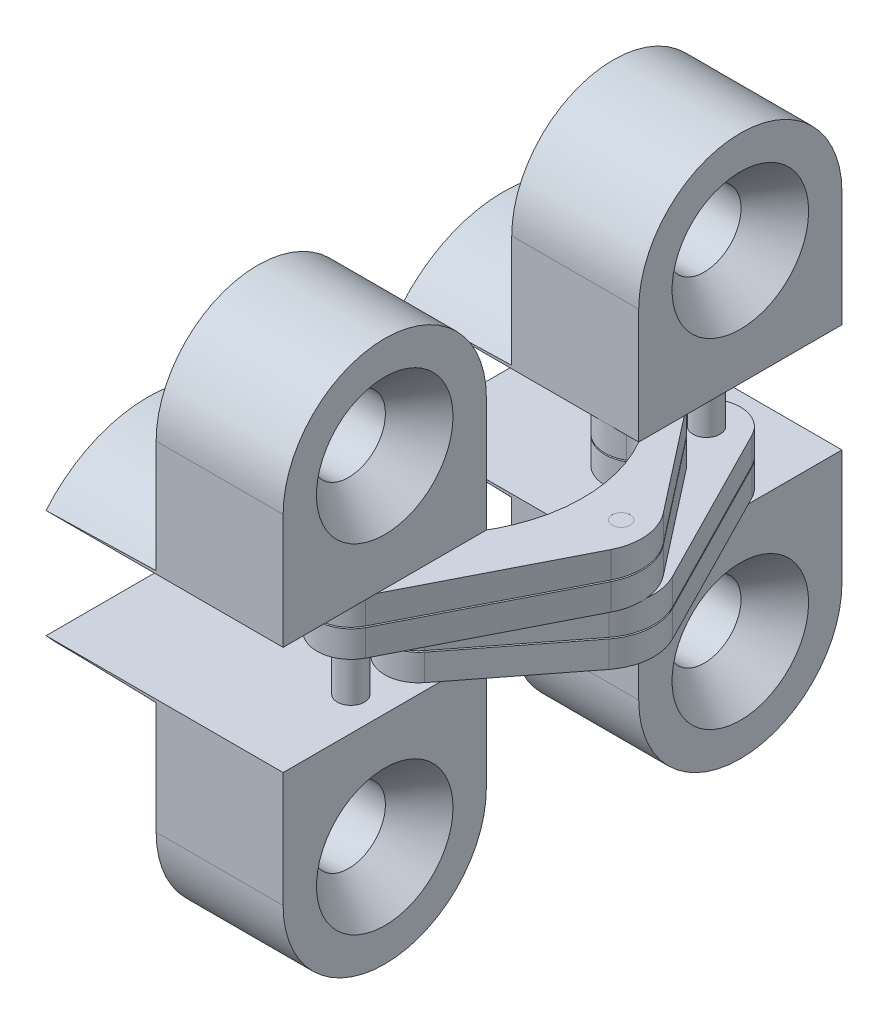
SolidWorks part; units mm, degrees
ref_plane "Front" through (0, 0, 0) normal (0, 0, 1) x (1, 0, 0)
ref_plane "Top" through (0, 0, 0) normal (0, 1, 0) x (1, 0, 0)
ref_plane "Right" through (0, 0, 0) normal (1, 0, 0) x (0, 0, -1)
sketch "Sketch1" plane through (0, 0, 0) normal (1, 0, 0) x (0, 0, -1)
  line L0 (-8.3344, 0) -> (8.3344, 0) construction
  line L1 (-11.9062, 2.54) -> (-4.7625, -2.54) construction
  line L2 (-11.9062, 2.54) -> (-4.7625, 2.54) construction
  line L3 (-11.9062, 2.54) -> (-11.9062, -2.54) construction
  line L4 (-11.9062, -2.54) -> (-4.7625, -2.54) construction
  line L5 (-4.7625, 2.54) -> (-4.7625, -2.54) construction
  line L6 (4.7625, 2.54) -> (11.9063, 2.54) construction
  line L7 (4.7625, 2.54) -> (4.7625, -2.54) construction
  line L8 (4.7625, -2.54) -> (11.9062, -2.54) construction
  line L9 (11.9063, 2.54) -> (11.9062, -2.54) construction
  line L10 (4.7625, 2.54) -> (11.9062, -2.54) construction
  line L11 (-4.7625, 2.54) -> (-5.9531, 2.54) construction
  line L12 (-5.9531, 2.54) -> (-5.9531, 3.7306) construction
  line L13 (-5.9531, 3.7306) -> (-7.1438, 3.7306) construction
  line L14 (-7.1438, 3.7306) -> (-7.1438, 2.54) construction
  line L15 (-7.1438, 2.54) -> (-11.9062, 2.54) construction
  line L16 (-11.9062, -2.54) -> (-7.1438, -2.54) construction
  line L17 (-7.1438, -2.54) -> (-7.1438, -3.7306) construction
  line L18 (-7.1438, -3.7306) -> (-5.9531, -3.7306) construction
  line L19 (-5.9531, -3.7306) -> (-5.9531, -2.54) construction
  line L20 (-5.9531, -2.54) -> (-4.7625, -2.54) construction
  line L21 (4.7625, 2.54) -> (5.9531, 2.54) construction
  line L22 (5.9531, 2.54) -> (5.9531, 3.7306) construction
  line L23 (5.9531, 3.7306) -> (7.1437, 3.7306) construction
  line L24 (7.1437, 3.7306) -> (7.1438, 2.54) construction
  line L25 (7.1438, 2.54) -> (11.9063, 2.54) construction
  line L26 (4.7625, -2.54) -> (5.9531, -2.54) construction
  line L27 (5.9531, -2.54) -> (5.9531, -3.7306) construction
  line L28 (5.9531, -3.7306) -> (7.1438, -3.7306) construction
  line L29 (7.1438, -3.7306) -> (7.1438, -2.54) construction
  line L30 (7.1438, -2.54) -> (11.9062, -2.54) construction
  line L31 (-8.3344, 0) -> (-4.7625, 0) construction
  line L32 (4.7625, 0) -> (8.3344, 0) construction
  line L33 (-6.5484, 3.7306) -> (-6.5484, 0) construction
  line L34 (6.5484, 3.7306) -> (6.5484, 0) construction
  line L35 (-3.5719, 7.9375) -> (-3.5719, -7.9375) construction
  line L36 (-13.0969, 7.9375) -> (-13.0969, -7.9375) construction
  line L37 (3.5719, 7.9375) -> (3.5719, -7.9375) construction
  line L38 (13.0969, 7.9375) -> (13.0969, -7.9375) construction
  line L39 (8.3344, 12.7) -> (-8.3344, 12.7) construction
  line L40 (-8.3344, -12.7) -> (8.3344, -12.7) construction
  line L41 (-13.0969, 7.9375) -> (-13.0969, -7.9375)
  line L42 (-3.5719, 7.9375) -> (-3.5719, -7.9375)
  line L43 (3.5719, 7.9375) -> (3.5719, -7.9375)
  line L44 (13.0969, 7.9375) -> (13.0969, -7.9375)
  line L45 (-4.7625, 2.54) -> (-4.7625, 0) construction
  line L46 (-4.7625, 1.27) -> (4.7625, 1.27) construction
  line L47 (-4.7625, 1.27) -> (-4.7625, -1.27) construction
  line L48 (-4.7625, -1.27) -> (4.7625, -1.27) construction
  line L49 (4.7625, 1.27) -> (4.7625, -1.27) construction
  arc A2 (-13.0969, 7.9375) -> (-3.5719, 7.9375) centre (-8.3344, 7.9375) cw
  arc A3 (-13.0969, -7.9375) -> (-3.5719, -7.9375) centre (-8.3344, -7.9375) ccw
  arc A4 (3.5719, 7.9375) -> (13.0969, 7.9375) centre (8.3344, 7.9375) cw
  arc A5 (3.5719, -7.9375) -> (13.0969, -7.9375) centre (8.3344, -7.9375) ccw
  point P45 (-3.5719, 0)
  point P54 (4.7625, 0.8467)
  point P55 (0, -12.7)
  point P56 (4.7625, 1.6933)
  point P57 (4.7625, -0.8467)
  point P58 (4.7625, -1.6933)
  dimension "D1" = 7.1438
  dimension "D2" = 5.08
  dimension "A" = 16.6687
  dimension "Leaf Ht" = 25.4
  dimension "Leaf Wd" = 9.525
  dimension "D3" = 0.8467
  dimension "D4" = 0.8467
  dimension "D5" = 0.8467
  dimension "D6" = 0.8467
extrude "Extrude1" add sketch "Sketch1" against normal blind 11.1125
sketch "Sketch16" plane through (0, 0, 0) normal (1, 0, 0) x (0, 0, -1)
  line L0 (-13.0969, 7.9375) -> (-13.0969, -7.9375) construction
  line L1 (-13.0969, 2.54) -> (13.0969, 2.54)
  line L2 (-13.0969, 2.54) -> (-13.0969, -2.54)
  line L3 (-13.0969, -2.54) -> (13.0969, -2.54)
  line L4 (13.0969, 2.54) -> (13.0969, -2.54)
  line L5 (13.0969, 7.9375) -> (13.0969, -7.9375) construction
  line L6 (-11.9062, 2.54) -> (-4.7625, 2.54) construction
  line L7 (4.7625, -2.54) -> (11.9062, -2.54) construction
extrude "Cut-Extrude1" cut sketch "Sketch16" against normal through all
ref_plane "Plane2" through (0, 0, 8.3344) normal (0, 0, 1) x (1, 0, 0)
ref_plane "Plane3" through (0, 0, -8.3344) normal (0, 0, 1) x (1, 0, 0)
ref_plane "Plane1" through (0, 1.27, 0) normal (0, 1, 0) x (-1, 0, 0)
sketch "Sketch4" plane through (0, 1.27, 0) normal (0, 1, 0) x (-1, 0, 0)
  line L0 (0, 8.3344) -> (0, -8.3344) construction
  line L1 (11.1125, 3.5719) -> (0, 3.5719) construction
  line L2 (-4.445, 0) -> (0.1733, 9.0556) construction
  line L4 (0.1733, -9.0556) -> (-4.445, 0) construction
  line L5 (-4.445, 0) -> (0.3352, 6.1351) construction
  line L8 (1.5875, 5.1594) -> (0.7938, 3.7846) construction
  line L9 (-3.175, 0) -> (-4.445, 0) construction
  line L11 (11.1125, 9.9219) -> (0, 9.9219) construction
  line L12 (1.5875, -8.3344) -> (1.5875, 8.3344) construction
  line L15 (11.1125, -3.5719) -> (0, -3.5719) construction
  line L18 (11.1125, 3.5719) -> (11.1125, 13.0969) construction
  line L19 (0, 13.0969) -> (0, 3.5719) construction
  line L20 (11.1125, 13.0969) -> (0, 13.0969) construction
  arc A0 (0.3352, 6.1351) -> (0.7938, 3.7846) centre (1.5875, 5.1594) cw construction
  arc A1 (0, -3.5719) -> (0, 3.5719) centre (6.1867, 0) cw construction
  arc A2 (0, 3.5719) -> (0.7938, 3.7846) centre (0.5032, 3.2813) cw construction
  circle A3 centre (1.5875, 8.3344) radius 0.635 construction
  circle A5 centre (1.5875, -8.3344) radius 1.5875 construction
  circle A8 centre (-2.7517, 0) radius 0.4233 construction
  circle A9 centre (1.5875, -8.3344) radius 0.635 construction
  circle A10 centre (1.5875, 5.1594) radius 0.635 construction
  circle A12 centre (1.5875, 8.3344) radius 1.5875 construction
  circle A14 centre (1.5875, -5.1594) radius 1.5875 construction
  dimension "D1" = 4.445
  dimension "D2" = 3.175
  dimension "D3" = 1.27
  dimension "D5" = 1.27
  dimension "D6" = 0.8467
  dimension "D7" = 3.175
  dimension "D8" = 30
sketch "Sketch5" plane through (0, 1.27, 0) normal (0, 1, 0) x (-1, 0, 0)
  line L0 (0.1733, -9.0556) -> (-4.445, 0) construction
  line L1 (0.1733, -9.0556) -> (-4.445, 0)
  line L2 (-4.445, 0) -> (0.3352, 6.1351)
  line L3 (2.8447, -7.365) -> (0.5293, -4.362)
  arc A0 (0.1733, -9.0556) -> (2.8447, -7.365) centre (1.5875, -8.3344) ccw
  arc A1 (0, 3.5719) -> (0.5293, -4.362) centre (6.1867, 0) ccw
  arc A2 (0.7938, 3.7846) -> (0.3352, 6.1351) centre (1.5875, 5.1594) ccw
  arc A3 (0, 3.5719) -> (0.7938, 3.7846) centre (0.5032, 3.2813) cw
  arc A4 (0, 3.5719) -> (0, -3.5719) centre (6.1867, 0) ccw construction
  circle A8 centre (1.5875, -8.3344) radius 0.635
  circle A9 centre (-2.7517, 0) radius 0.4233
  circle A12 centre (1.5875, 5.1594) radius 0.635
  circle A13 centre (1.5875, 5.1594) radius 0.635 construction
  circle A15 centre (1.5875, -8.3344) radius 0.635 construction
  arc A16 (0.7938, 3.7846) -> (0.3352, 6.1351) centre (1.5875, 5.1594) ccw construction
  circle A18 centre (-2.7517, 0) radius 0.4233 construction
  arc A21 (0.7938, 3.7846) -> (0, 3.5719) centre (0.5032, 3.2813) ccw construction
extrude "Extrude3" [suppressed] add sketch "Sketch5" along normal up to vertex separate body
sketch "Sketch6" [suppressed] plane through (0, 3.5719, 0) normal (0, 1, 0) x (-1, 0, 0)
  line L0 (-4.6037, 0) -> (0.1769, 9.261) construction
  line L1 (0.563, 4.61) -> (2.8438, 7.5623)
  line L3 (0.3356, -6.334) -> (-4.6037, 0)
  line L4 (-4.6037, 0) -> (0.1769, 9.261)
  line L5 (-4.6037, 0) -> (0.3356, 6.334) construction
  line L6 (1.5875, -8.5328) -> (1.5875, 8.5328) construction
  arc A0 (0.1769, 9.261) -> (2.8438, 7.5623) centre (1.5875, 8.5328) cw
  arc A2 (0.3356, -6.334) -> (0.7938, -3.983) centre (1.5875, -5.3578) ccw
  circle A3 centre (1.5875, 8.5328) radius 1.5875 construction
  arc A4 (0, -3.7703) -> (0.563, 4.61) centre (6.5304, 0) cw
  arc A6 (0, 3.7703) -> (0, -3.7703) centre (6.5304, 0) ccw construction
  arc A7 (0.7938, -3.983) -> (0, -3.7703) centre (0.5032, -3.4798) cw
  circle A8 centre (1.5875, -5.3578) radius 0.635
  circle A9 centre (1.5875, 5.3578) radius 0.635 construction
  circle A10 centre (-2.9104, 0) radius 0.4233
  circle A12 centre (1.5875, 8.5328) radius 0.635
  arc A13 (0.7938, 3.983) -> (0, 3.7703) centre (0.5032, 3.4798) ccw construction
  circle A16 centre (-2.9104, 0) radius 0.4233 construction
extrude "Extrude13" [suppressed] add sketch "Sketch6" against normal up to vertex separate body
sketch "Sketch7" [suppressed] plane through (0, 0, 0) normal (0, 1, 0) x (-1, 0, 0)
  line L0 (0.1769, -9.261) -> (-4.6037, 0) construction
  line L1 (0.3356, 6.334) -> (-4.6037, 0)
  line L2 (-4.6037, 0) -> (0.1769, -9.261)
  line L3 (-4.6037, 0) -> (0.3356, 6.334) construction
  line L4 (2.8438, -7.5623) -> (0.563, -4.61)
  arc A0 (0.3356, 6.334) -> (0.7938, 3.983) centre (1.5875, 5.3578) cw
  circle A1 centre (1.5875, -8.5328) radius 0.635 construction
  arc A2 (0.1769, -9.261) -> (2.8438, -7.5623) centre (1.5875, -8.5328) ccw
  arc A4 (0.563, -4.61) -> (0, 3.7703) centre (6.5304, 0) cw
  arc A5 (0, 3.7703) -> (0.7938, 3.983) centre (0.5032, 3.4798) cw
  arc A6 (0.7938, 3.983) -> (0, 3.7703) centre (0.5032, 3.4798) ccw construction
  circle A7 centre (1.5875, 5.3578) radius 0.635 construction
  circle A8 centre (-2.9104, 0) radius 0.4233 construction
  circle A9 centre (1.5875, 5.3578) radius 0.635
  arc A10 (0, 3.7703) -> (0, -3.7703) centre (6.5304, 0) ccw construction
  circle A15 centre (1.5875, -8.5328) radius 0.635
  circle A17 centre (-2.9104, 0) radius 0.4233
extrude "Extrude5" [suppressed] add sketch "Sketch7" against normal up to vertex separate body
sketch "Sketch17" [suppressed] plane through (0, -3.5719, 0) normal (0, -1, 0) x (1, 0, 0)
  line L0 (-0.3356, -6.334) -> (4.6037, 0)
  line L1 (4.6037, 0) -> (-0.1769, 9.261)
  line L2 (4.6037, 0) -> (-0.1769, 9.261) construction
  line L3 (-0.563, 4.61) -> (-2.8438, 7.5623)
  arc A0 (-0.3356, -6.334) -> (-0.7938, -3.983) centre (-1.5875, -5.3578) cw
  arc A1 (-2.8438, 7.5623) -> (-0.1769, 9.261) centre (-1.5875, 8.5328) cw
  arc A2 (0, -3.7703) -> (-0.563, 4.61) centre (-6.5304, 0) ccw
  arc A3 (-0.7938, -3.983) -> (-0.3356, -6.334) centre (-1.5875, -5.3578) ccw construction
  arc A6 (-0.7938, -3.983) -> (0, -3.7703) centre (-0.5032, -3.4798) ccw
  arc A7 (0, -3.7703) -> (0, 3.7703) centre (-6.5304, 0) ccw construction
  arc A8 (-0.7938, -3.983) -> (0, -3.7703) centre (-0.5032, -3.4798) ccw construction
  circle A9 centre (-1.5875, -5.3578) radius 0.635
  circle A10 centre (2.9104, 0) radius 0.4233
  circle A11 centre (-1.5875, 8.5328) radius 0.635
  circle A12 centre (-1.5875, 8.5328) radius 0.635 construction
  circle A13 centre (-1.5875, -5.3578) radius 0.635 construction
  circle A14 centre (2.9104, 0) radius 0.4233 construction
extrude "Extrude14" [suppressed] add sketch "Sketch17" along normal up to surface (3.5719 mm away) separate body
fillet "Fillet3" [suppressed] radius 2.54
fillet "Fillet4" [suppressed] radius 2.54
fillet "Fillet5" [suppressed] radius 2.54
fillet "Fillet6" [suppressed] radius 2.54
sketch "Sketch41" plane through (0, 0, 0) normal (1, 0, 0) x (0, 0, -1)
  line L0 (-13.0969, 7.9375) -> (-13.0969, -7.9375) construction
  line L1 (-13.0969, 1.7251) -> (13.0969, 1.7251)
  line L2 (-13.0969, 1.7251) -> (-13.0969, 1.6616)
  line L3 (-13.0969, 1.6616) -> (13.0969, 1.6616)
  line L4 (13.0969, 1.7251) -> (13.0969, 1.6616)
  line L5 (13.0969, 7.9375) -> (13.0969, -7.9375) construction
  line L6 (13.0969, 1.7251) -> (13.0969, 2.54) construction
  line L7 (-13.0969, 1.7251) -> (-13.0969, 2.54) construction
  line L8 (4.7625, 1.7251) -> (4.7625, 1.6616) construction
  line L9 (4.7625, 2.54) -> (4.7625, -2.54) construction
  line L10 (4.7625, 1.6616) -> (4.7625, 1.27) construction
  line L11 (-13.0969, 2.1484) -> (13.0969, 2.1484)
  line L12 (-13.0969, 2.1484) -> (-13.0969, 2.0849)
  line L13 (-13.0969, 2.0849) -> (13.0969, 2.0849)
  line L14 (13.0969, 2.1484) -> (13.0969, 2.0849)
  line L15 (-13.0969, 0.8784) -> (13.0969, 0.8784)
  line L16 (-13.0969, 0.8784) -> (-13.0969, 0.8149)
  line L17 (-13.0969, 0.8149) -> (13.0969, 0.8149)
  line L18 (13.0969, 0.8784) -> (13.0969, 0.8149)
  line L19 (-13.0969, 0.4551) -> (13.0969, 0.4551)
  line L20 (-13.0969, 0.4551) -> (-13.0969, 0.3916)
  line L21 (-13.0969, 0.3916) -> (13.0969, 0.3916)
  line L22 (13.0969, 0.4551) -> (13.0969, 0.3916)
  line L23 (-13.0969, -0.3916) -> (13.0969, -0.3916)
  line L24 (-13.0969, -0.3916) -> (-13.0969, -0.4551)
  line L25 (-13.0969, -0.4551) -> (13.0969, -0.4551)
  line L26 (13.0969, -0.3916) -> (13.0969, -0.4551)
  line L27 (-13.0969, -0.8149) -> (13.0969, -0.8149)
  line L28 (-13.0969, -0.8149) -> (-13.0969, -0.8784)
  line L29 (-13.0969, -0.8784) -> (13.0969, -0.8784)
  line L30 (13.0969, -0.8149) -> (13.0969, -0.8784)
  line L31 (-13.0969, -1.6616) -> (13.0969, -1.6616)
  line L32 (-13.0969, -1.6616) -> (-13.0969, -1.7251)
  line L33 (-13.0969, -1.7251) -> (13.0969, -1.7251)
  line L34 (13.0969, -1.6616) -> (13.0969, -1.7251)
  line L35 (-13.0969, -2.0849) -> (13.0969, -2.0849)
  line L36 (-13.0969, -2.0849) -> (-13.0969, -2.1484)
  line L37 (-13.0969, -2.1484) -> (13.0969, -2.1484)
  line L38 (13.0969, -2.0849) -> (13.0969, -2.1484)
  line L39 (4.7625, 2.1484) -> (4.7625, 2.54) construction
  line L40 (4.7625, 1.27) -> (4.7625, 0.8784) construction
  line L41 (4.7625, 0) -> (4.7625, 0.3916) construction
  line L42 (4.7625, 0) -> (4.7625, -0.3916) construction
  line L43 (4.7625, -0.8784) -> (4.7625, -1.27) construction
  line L44 (4.7625, -1.27) -> (4.7625, -1.6616) construction
  line L45 (4.7625, -2.54) -> (4.7625, -2.1484) construction
  dimension "D1" = 0.0635
  dimension "D2" = 0.0635
  dimension "D3" = 0.0635
  dimension "D4" = 0.0635
  dimension "D5" = 0.0635
  dimension "D6" = 0.0635
  dimension "D7" = 0.0635
  dimension "D8" = 0.0635
extrude "Cut-Extrude4" [suppressed] cut sketch "Sketch41" against normal through all and the other way through all
sketch "Sketch34" plane through (0, 2.54, 0) normal (0, -1, 0) x (1, 0, 0)
  line L0 (-0.1733, 9.0556) -> (4.445, 0)
  line L1 (-0.3352, -6.1351) -> (4.445, 0)
  line L2 (-0.5293, 4.362) -> (-2.8447, 7.365)
  arc A0 (-0.1733, 9.0556) -> (-2.8447, 7.365) centre (-1.5875, 8.3344) ccw
  circle A1 centre (-1.5875, 8.3344) radius 1.5875 construction
  arc A2 (-0.7938, -3.7846) -> (-0.3352, -6.1351) centre (-1.5875, -5.1594) ccw
  circle A3 centre (-1.5875, -5.1594) radius 1.5875 construction
  arc A4 (-0.3352, 6.1351) -> (-0.7938, 3.7846) centre (-1.5875, 5.1594) ccw construction
  arc A5 (-0.7938, -3.7846) -> (0, -3.5719) centre (-0.5032, -3.2813) ccw
  arc A6 (0, -3.5719) -> (-0.5293, 4.362) centre (-6.1867, 0) ccw
  arc A7 (0, -3.5719) -> (0, 3.5719) centre (-6.1867, 0) ccw construction
  circle A8 centre (-1.5875, 8.3344) radius 0.635
  circle A9 centre (-1.5875, 8.3344) radius 0.635 construction
  circle A10 centre (-1.5875, -5.1594) radius 0.635
  circle A11 centre (2.7517, 0) radius 0.4233
  circle A12 centre (2.7517, 0) radius 0.4233 construction
extrude "Extrude18" add sketch "Sketch34" along normal up to vertex (2.54 mm away) separate body up to point (0, 0, 4.7625)
sketch "Sketch35" plane through (0, 0, 0) normal (0, -1, 0) x (1, 0, 0)
  line L0 (-2.8447, -7.365) -> (-0.5293, -4.362)
  line L1 (-0.1733, -9.0556) -> (4.445, 0)
  line L2 (4.445, 0) -> (-0.3352, 6.1351)
  arc A0 (-2.8447, -7.365) -> (-0.1733, -9.0556) centre (-1.5875, -8.3344) ccw
  circle A1 centre (-1.5875, -8.3344) radius 1.5875 construction
  arc A2 (-0.7938, 3.7846) -> (-0.3352, 6.1351) centre (-1.5875, 5.1594) cw
  arc A3 (-0.3352, 6.1351) -> (-0.7938, 3.7846) centre (-1.5875, 5.1594) ccw construction
  arc A4 (-0.5293, -4.362) -> (0, 3.5719) centre (-6.1867, 0) ccw
  arc A5 (0, -3.5719) -> (0, 3.5719) centre (-6.1867, 0) ccw construction
  arc A6 (-0.7938, 3.7846) -> (0, 3.5719) centre (-0.5032, 3.2813) cw
  arc A7 (0, 3.5719) -> (-0.7938, 3.7846) centre (-0.5032, 3.2813) ccw construction
  circle A8 centre (-1.5875, -8.3344) radius 0.635
  circle A9 centre (-1.5875, -8.3344) radius 0.635 construction
  circle A10 centre (-1.5875, 5.1594) radius 0.635
  circle A11 centre (-1.5875, 5.1594) radius 0.635 construction
  circle A12 centre (2.7517, 0) radius 0.4233
  circle A13 centre (2.7517, 0) radius 0.4233 construction
extrude "Extrude19" add sketch "Sketch35" along normal up to vertex (2.54 mm away) separate body up to point (0, -2.54, 4.7625)
fillet "Fillet7" radius 2.54 1 edges at (4.445, 1.27, 0)
fillet "Fillet8" radius 2.54 1 edges at (4.445, -1.27, 0)
ref_plane "Plane4" through (0, 1.6933, 0) normal (0, 1, 0) x (-1, 0, 0)
sketch "Sketch39" plane through (0, 1.6933, 0) normal (0, 1, 0) x (-1, 0, 0)
  line L0 (0.1733, 9.0556) -> (-4.445, 0)
  line L1 (-4.445, 0) -> (0.3352, -6.1351)
  line L2 (0.5293, 4.362) -> (2.8447, 7.365)
  arc A0 (2.8447, 7.365) -> (0.1733, 9.0556) centre (1.5875, 8.3344) ccw
  circle A1 centre (1.5875, 8.3344) radius 1.5875 construction
  circle A2 centre (1.5875, -5.1594) radius 1.5875 construction
  arc A3 (0.3352, -6.1351) -> (0.7938, -3.7846) centre (1.5875, -5.1594) ccw
  arc A4 (0.7938, -3.7846) -> (0, -3.5719) centre (0.5032, -3.2813) cw
  arc A5 (0, 3.5719) -> (0, -3.5719) centre (6.1867, 0) ccw construction
  arc A6 (0, -3.5719) -> (0.5293, 4.362) centre (6.1867, 0) cw
  circle A7 centre (1.5875, -5.1594) radius 0.635
  circle A8 centre (1.5875, 8.3344) radius 0.635
  circle A9 centre (-2.7517, 0) radius 0.4233
  circle A10 centre (-2.7517, 0) radius 0.4233 construction
  circle A11 centre (1.5875, 8.3344) radius 0.635 construction
extrude "Extrude20" [suppressed] add sketch "Sketch39" along normal up to surface (2.1167 mm away) separate body
sketch "Sketch40" [suppressed] plane through (0, 4.2333, 0) normal (0, -1, 0) x (1, 0, 0)
  line L0 (-0.2378, -12.0872) -> (6.0325, 0)
  line L1 (6.0325, 0) -> (-0.4574, 8.1934)
  line L2 (-3.7929, -9.8201) -> (-0.7057, -5.816)
  arc A0 (-0.2378, -12.0872) -> (-3.7929, -9.8201) centre (-2.1167, -11.1125) cw
  circle A1 centre (-2.1167, -11.1125) radius 2.1167 construction
  arc A2 (-0.4574, 8.1934) -> (-1.0583, 5.0461) centre (-2.1167, 6.8792) ccw
  arc A3 (-1.0583, 5.0461) -> (0, 4.7625) centre (-0.671, 4.3751) cw
  arc A4 (0, 4.7625) -> (-0.7057, -5.816) centre (-8.2489, 0) cw
  arc A5 (-0.4574, 8.1934) -> (-1.0583, 5.0461) centre (-2.1167, 6.8792) ccw construction
  arc A6 (0, 4.7625) -> (-1.0583, 5.0461) centre (-0.671, 4.3751) ccw construction
  arc A7 (0, -4.7625) -> (0, 4.7625) centre (-8.2489, 0) ccw construction
  circle A8 centre (-2.1167, -11.1125) radius 0.8467
  circle A9 centre (-2.1167, 6.8792) radius 0.8467
  circle A10 centre (4.1981, 0) radius 0.5644
  circle A11 centre (4.1981, 0) radius 0.5644 construction
  circle A12 centre (-2.1167, -11.1125) radius 0.8467 construction
  circle A13 centre (-2.1167, 6.8792) radius 0.8467 construction
extrude "Extrude21" [suppressed] add sketch "Sketch40" along normal up to vertex separate body
pattern_linear "LPattern1" [suppressed] count 3 spacing 1.6933 along (0, -1, 0)
fillet "Fillet9" [suppressed] radius 2.54
fillet "Fillet10" [suppressed] radius 2.54
fillet "Fillet11" [suppressed] radius 2.54
fillet "Fillet12" [suppressed] radius 2.54
fillet "Fillet13" [suppressed] radius 2.54
fillet "Fillet14" [suppressed] radius 2.54
sketch "Sketch13" plane through (0, -2.54, 0) normal (0, 1, 0) x (-1, 0, 0)
  circle A0 centre (1.5875, 8.3344) radius 0.635
  circle A2 centre (1.5875, 5.1594) radius 0.635
  circle A4 centre (1.5875, -8.3344) radius 0.635
  circle A6 centre (1.5875, -5.1594) radius 0.635
  circle A8 centre (1.5875, 8.3344) radius 0.635 construction
extrude "Extrude11" add sketch "Sketch13" along normal up to surface (5.08 mm away) separate body up to face at (-5.5562, 2.54, 8.3344)
sketch "Sketch38" plane through (0, 0, 0) normal (1, 0, 0) x (0, 0, -1)
  line L0 (-13.0969, 7.9375) -> (-13.0969, -7.9375) construction
  line L1 (-13.0969, 1.3018) -> (13.0969, 1.3018)
  line L2 (-13.0969, 1.3018) -> (-13.0969, 1.2382)
  line L3 (-13.0969, 1.2382) -> (13.0969, 1.2383)
  line L4 (13.0969, 1.3018) -> (13.0969, 1.2383)
  line L5 (13.0969, 7.9375) -> (13.0969, -7.9375) construction
  line L6 (0, 1.2383) -> (0, -1.2383) construction
  line L7 (-13.0969, -1.2382) -> (13.0969, -1.2383)
  line L8 (-13.0969, -1.2382) -> (-13.0969, -1.3018)
  line L9 (-13.0969, -1.3018) -> (13.0969, -1.3018)
  line L10 (13.0969, -1.2383) -> (13.0969, -1.3018)
  line L11 (0, 1.2383) -> (0, 1.3017) construction
  dimension "D1" = 0.0635
  dimension "D2" = 0.0635
extrude "Cut-Extrude3" cut sketch "Sketch38" against normal through all and the other way through all
sketch "Sketch19" plane through (0, 0, 0) normal (1, 0, 0) x (0, 0, -1)
  line L0 (-8.3344, 7.9375) -> (8.3344, -7.9375) construction
  line L1 (8.3344, 7.9375) -> (-8.3344, -7.9375) construction
  line L2 (-25.0031, 1.27) -> (-25.0031, -1.27) construction
  line L3 (25.0031, 1.27) -> (25.0031, -1.27) construction
  line L4 (-25.0031, 0) -> (25.0031, 0) construction
  line L5 (-3.5719, 7.9375) -> (-3.5719, -7.9375) construction
  point P0 (-8.3344, 7.9375)
  point P1 (8.3344, 7.9375)
  point P2 (-8.3344, -7.9375)
  point P3 (8.3344, -7.9375)
  point P12 (25.0031, 1.27)
  point P13 (10.7156, 7.9375)
  point P14 (-10.7156, 7.9375)
  point P15 (-25.0031, 1.27)
  point P16 (-25.0031, -1.27)
  point P17 (-10.7156, -7.9375)
  point P18 (10.7156, -7.9375)
  point P19 (25.0031, -1.27)
  point P26 (0, 0)
  dimension "D1" = 14.2875
  dimension "Hole Dist1" = 15.875
  dimension "Hole Dist2" = 2.54
  dimension "D2" = 14.2875
  dimension "D3" = 7.1437
hole_wizard "CSK for #10 Flat Head Machine Screw1" [suppressed] positions "3DSketch1" profile "Sketch20" countersink size "#10" standard "Ansi Inch"
sketch3d "3DSketch1"
  point P0 (0, 47.625, 29.3688)
  point P3 (0, 34.0604, 15.0812)
  point P6 (0, 34.0604, -15.0812)
  point P9 (0, 47.625, -29.3688)
  point P12 (0, -47.625, 29.3687)
  point P15 (0, -34.0604, 15.0812)
  point P18 (0, -34.0604, -15.0812)
  point P21 (0, -47.625, -29.3688)
sketch "Sketch20" plane through (0, 47.625, 29.3688) normal (0, 1, 0) x (0, 0, -1)
  line L0 (0, 0) -> (0, 42.0688)
  line L1 (0, 42.0688) -> (2.5527, 42.0688)
  line L2 (2.5527, 42.0688) -> (2.5527, 2.6882)
  line L3 (2.5527, 2.6882) -> (4.8895, 0)
  line L5 (4.8895, 0) -> (0, 0)
  line L6 (-2.5527, 2.6882) -> (-4.8895, 0) construction
  line L11 (0, -6.35) -> (0, 107.95) construction
  dimension "Thru Hole Dia." = 5.1054
  dimension "Thru Hole Depth" = 42.0688
  dimension "Near C'Sink Dia." = 9.779
  dimension "Near C'Sink Angle" = 82
hole_wizard "CSK for 1/4 Flat Head Machine Screw1" [suppressed] positions "3DSketch4" profile "Sketch23" countersink size "1/4" standard "Ansi Inch"
sketch3d "3DSketch4"
  point P0 (0, 12.7, 11.1125)
  point P16 (0, 12.7, -11.1125)
  point P21 (0, -12.7, 11.1125)
  point P26 (0, -12.7, -11.1125)
sketch "Sketch23" plane through (0, 12.7, 11.1125) normal (0, 1, 0) x (0, 0, -1)
  line L0 (0, 0) -> (0, 16.6687)
  line L1 (0, 16.6687) -> (3.3782, 16.6687)
  line L2 (3.3782, 16.6687) -> (3.3782, 3.5209)
  line L3 (3.3782, 3.5209) -> (6.4389, 0)
  line L5 (6.4389, 0) -> (0, 0)
  line L6 (-3.3782, 3.5209) -> (-6.4389, 0) construction
  line L11 (0, -6.35) -> (0, 107.95) construction
  dimension "Thru Hole Dia." = 6.7564
  dimension "Thru Hole Depth" = 16.6687
  dimension "Near C'Sink Dia." = 12.8778
  dimension "Near C'Sink Angle" = 82
hole_wizard "CSK for #10 Flat Head Machine Screw2" [suppressed] positions "Sketch25" profile "Sketch24" countersink size "#10" standard "Ansi Inch"
sketch "Sketch25" plane through (0, 7.9375, 8.3344) normal (1, 0, 0) x (0, 0, -1)
  point P0 (-2.7781, 4.7625)
  point P4 (19.4469, 4.7625)
  point P7 (-2.7781, -20.6375)
  point P10 (19.4469, -20.6375)
sketch "Sketch24" plane through (0, 12.7, 11.1125) normal (0, 1, 0) x (0, 0, -1)
  line L0 (0, 0) -> (0, 16.6687)
  line L1 (0, 16.6687) -> (2.5527, 16.6687)
  line L2 (2.5527, 16.6687) -> (2.5527, 2.6882)
  line L3 (2.5527, 2.6882) -> (4.8895, 0)
  line L5 (4.8895, 0) -> (0, 0)
  line L6 (-2.5527, 2.6882) -> (-4.8895, 0) construction
  line L11 (0, -6.35) -> (0, 107.95) construction
  dimension "Thru Hole Dia." = 5.1054
  dimension "Thru Hole Depth" = 16.6687
  dimension "Near C'Sink Dia." = 9.779
  dimension "Near C'Sink Angle" = 82
hole_wizard "CSK for #8 Flat Head Machine Screw1" [suppressed] positions "Sketch27" profile "Sketch26" countersink size "#8" standard "Ansi Inch"
sketch "Sketch27" plane through (0, 0, 0) normal (1, 0, 0) x (0, 0, -1)
  point P0 (-11.1125, 12.7)
  point P4 (11.1125, 12.7)
  point P7 (-11.1125, -12.7)
  point P10 (11.1125, -12.7)
sketch "Sketch26" plane through (0, 12.7, 11.1125) normal (0, 1, 0) x (0, 0, -1)
  line L0 (0, 0) -> (0, 16.6687)
  line L1 (0, 16.6687) -> (2.2479, 16.6687)
  line L2 (2.2479, 16.6687) -> (2.2479, 2.2645)
  line L3 (2.2479, 2.2645) -> (4.2164, 0)
  line L5 (4.2164, 0) -> (0, 0)
  line L6 (-2.2479, 2.2645) -> (-4.2164, 0) construction
  line L11 (0, -6.35) -> (0, 107.95) construction
  dimension "Thru Hole Dia." = 4.4958
  dimension "Thru Hole Depth" = 16.6687
  dimension "Near C'Sink Dia." = 8.4328
  dimension "Near C'Sink Angle" = 82
hole_wizard "CSK for #6 Flat Head Machine Screw1" [suppressed] positions "Sketch29" profile "Sketch28" countersink size "#6" standard "Ansi Inch"
sketch "Sketch29" plane through (0, 0, 0) normal (1, 0, 0) x (0, 0, -1)
  point P0 (-11.1125, 12.7)
  point P4 (11.1125, 12.7)
  point P6 (-11.1125, -12.7)
  point P9 (11.1125, -12.7)
sketch "Sketch28" plane through (0, 12.7, 11.1125) normal (0, 1, 0) x (0, 0, -1)
  line L0 (0, 0) -> (0, 16.6687)
  line L1 (0, 16.6687) -> (1.8986, 16.6687)
  line L2 (1.8986, 16.6687) -> (1.8986, 1.892)
  line L3 (1.8986, 1.892) -> (3.5433, 0)
  line L5 (3.5433, 0) -> (0, 0)
  line L6 (-1.8986, 1.892) -> (-3.5433, 0) construction
  line L11 (0, -6.35) -> (0, 107.95) construction
  dimension "Thru Hole Dia." = 3.7973
  dimension "Thru Hole Depth" = 16.6687
  dimension "Near C'Sink Dia." = 7.0866
  dimension "Near C'Sink Angle" = 82
hole_wizard "CSK for #5 Flat Head Machine Screw1" positions "Sketch31" profile "Sketch30" countersink size "#5" standard "Ansi Inch" end condition through all
sketch "Sketch31" plane through (0, 0, 0) normal (1, 0, 0) x (0, 0, -1)
  point P0 (-8.3344, 7.9375)
  point P4 (8.3344, 7.9375)
  point P7 (-8.3344, -7.9375)
  point P10 (8.3344, -7.9375)
sketch "Sketch30" plane through (0, 7.9375, 8.3344) normal (0, 1, 0) x (0, 0, -1)
  line L0 (0, 0) -> (0, 11.1125)
  line L1 (0, 11.1125) -> (1.7272, 11.1125)
  line L2 (1.7272, 11.1125) -> (1.7272, 1.6947)
  line L3 (1.7272, 1.6947) -> (3.2004, 0)
  line L5 (3.2004, 0) -> (0, 0)
  line L6 (-1.7272, 1.6947) -> (-3.2004, 0) construction
  line L11 (0, -6.35) -> (0, 107.95) construction
  dimension "Thru Hole Dia." = 3.4544
  dimension "Thru Hole Depth" = 11.1125
  dimension "Near C'Sink Dia." = 6.4008
  dimension "Near C'Sink Angle" = 82
sketch "Sketch33" plane through (0, 2.54, 0) normal (0, -1, 0) x (1, 0, 0)
  circle A0 centre (2.7517, 0) radius 0.4233
  circle A1 centre (2.7517, 0) radius 0.4233 construction
extrude "Extrude17" add sketch "Sketch33" along normal up to surface (5.08 mm away) separate body up to face at (-5.5562, -2.54, 8.3344)
sketch "Sketch32" plane through (-11.1125, 0, 0) normal (-1, 0, 0) x (0, 0, 1)
  line L0 (-8.3344, 4.7625) -> (-8.3344, -4.7625) construction
  line L1 (-13.0969, 2.54) -> (-13.0969, 7.9375) construction
  line L2 (8.3344, 4.7625) -> (8.3344, -4.7625) construction
  line L3 (-13.0969, 2.54) -> (-13.0969, -2.54)
  line L4 (-3.5719, 2.54) -> (-3.5719, -2.54)
  line L5 (3.5719, 2.54) -> (3.5719, -2.54)
  line L6 (13.0969, 2.54) -> (13.0969, -2.54)
  line L7 (3.5719, 2.54) -> (3.5719, 7.9375) construction
  line L8 (13.0969, 7.9375) -> (13.0969, 2.54) construction
  line L9 (-3.5719, 7.9375) -> (-3.5719, -7.9375) construction
  arc A0 (13.0969, 2.54) -> (3.5719, 2.54) centre (8.3344, -1.4514) ccw
  arc A1 (-13.0969, 2.54) -> (-3.5719, 2.54) centre (-8.3344, -1.4514) cw
  arc A2 (3.5719, -2.54) -> (13.0969, -2.54) centre (8.3344, 1.4514) ccw
  arc A3 (-13.0969, -2.54) -> (-3.5719, -2.54) centre (-8.3344, 1.4514) ccw
  point P22 (-8.3344, 0)
  dimension "Back" = 9.525
extrude "Cut-Extrude2" cut sketch "Sketch32" against normal offset from surface 5.9531 draft 1 flip side to cut
sketch "Sketch43" [suppressed] plane through (-11.5094, 0, 0) normal (-1, 0, 0) x (0, 0, 1)
  line L0 (3.7703, 16.6687) -> (3.7703, -16.6687) construction
  line L1 (3.7703, 11.1125) -> (17.4625, 11.1125)
  line L2 (3.7703, 11.1125) -> (3.7703, 6.35)
  line L3 (3.7703, 6.35) -> (17.4625, 6.35)
  line L4 (17.4625, 11.1125) -> (17.4625, 6.35)
  line L5 (13.2953, 16.6687) -> (13.2953, -16.6687) construction
  line L6 (7.9375, -7.1438) -> (13.2953, -7.1438)
  line L7 (7.9375, -7.1438) -> (7.9375, -11.1125)
  line L8 (7.9375, -11.1125) -> (13.2953, -11.1125)
  line L9 (13.2953, -7.1438) -> (13.2953, -11.1125)
  line L10 (-13.2953, 16.6687) -> (-13.2953, -16.6687) construction
  line L11 (-13.2953, 11.1125) -> (-3.7703, 11.1125)
  line L12 (-13.2953, 11.1125) -> (-13.2953, 6.35)
  line L13 (-13.2953, 6.35) -> (-3.7703, 6.35)
  line L14 (-3.7703, 11.1125) -> (-3.7703, 6.35)
  line L15 (-3.7703, 16.6687) -> (-3.7703, -16.6687) construction
  line L16 (-17.4625, -6.35) -> (-3.7703, -6.35)
  line L17 (-17.4625, -6.35) -> (-17.4625, -11.1125)
  line L18 (-17.4625, -11.1125) -> (-3.7703, -11.1125)
  line L19 (-3.7703, -6.35) -> (-3.7703, -11.1125)
  line L20 (10.6164, 11.1125) -> (10.6164, -11.1125) construction
  line L21 (-17.4625, 6.35) -> (-4.7625, 6.35) construction
  line L22 (12.1047, -7.1438) -> (4.9609, -7.1438) construction
  point P30 (10.6164, 0)
  dimension "D1" = 9.525
extrude "Cut-Extrude5" [suppressed] cut sketch "Sketch43" against normal blind 5.9531 flip side to cut
sketch "Sketch44" plane through (0, 0, 0) normal (1, 0, 0) x (0, 0, -1)
  line L0 (-13.0969, 7.9375) -> (-13.0969, -7.9375) construction
  line L1 (-13.0969, 4.9213) -> (-9.9219, 4.9213)
  line L2 (-13.0969, 4.9213) -> (-13.0969, 2.54)
  line L3 (-13.0969, 2.54) -> (-9.9219, 2.54)
  line L4 (-9.9219, 4.9213) -> (-9.9219, 2.54)
  line L5 (13.0969, 7.9375) -> (13.0969, -7.9375) construction
  line L6 (13.0969, 4.9213) -> (9.9219, 4.9213)
  line L7 (13.0969, 4.9213) -> (13.0969, 2.54)
  line L8 (13.0969, 2.54) -> (9.9219, 2.54)
  line L9 (9.9219, 4.9213) -> (9.9219, 2.54)
  line L10 (-11.9062, -2.54) -> (-4.7625, -2.54) construction
  line L11 (-13.0969, -2.54) -> (-9.9219, -2.54)
  line L12 (-13.0969, -2.54) -> (-13.0969, -4.9213)
  line L13 (-13.0969, -4.9213) -> (-9.9219, -4.9213)
  line L14 (-9.9219, -2.54) -> (-9.9219, -4.9213)
  line L15 (13.0969, -2.54) -> (9.9219, -2.54)
  line L16 (13.0969, -2.54) -> (13.0969, -4.9213)
  line L17 (13.0969, -4.9213) -> (9.9219, -4.9213)
  line L18 (9.9219, -2.54) -> (9.9219, -4.9213)
  line L19 (-11.9062, 2.54) -> (-4.7625, 2.54) construction
  line L20 (4.7625, 2.54) -> (11.9063, 2.54) construction
  line L21 (4.7625, -2.54) -> (11.9062, -2.54) construction
  point P28 (-9.9219, 3.7306)
extrude "Cut-Extrude6" [suppressed] cut sketch "Sketch44" against normal blind 1.27
equation "\"D1@Sketch1\" = \"Leaf Wd@Sketch1\"*.75"
equation "\"D1@Sketch4\" = \"D1@Extrude1\"/2.5"
equation "\"D5@Sketch4\" = \"D2@Sketch4\"/2.5"
equation "\"D6@Sketch4\" = \"D5@Sketch4\"/1.5"
equation "\"D7@Sketch4\" = \"Leaf Wd@Sketch1\"/3"
equation "\"D3@Sketch1\" = \"D2@Sketch1\"/6"
equation "\"D4@Sketch1\" = \"D3@Sketch1\""
equation "\"D5@Sketch1\" = \"D3@Sketch1\""
equation "\"D6@Sketch1\" = \"D3@Sketch1\""
equation "\"D3@LPattern1\" = \"D3@Sketch1\"*2"
equation "\"D1@Sketch43\" = \"Back@Sketch32\""
equation "\"D1@Cut-Extrude5\" = \"D1@Cut-Extrude2\""
